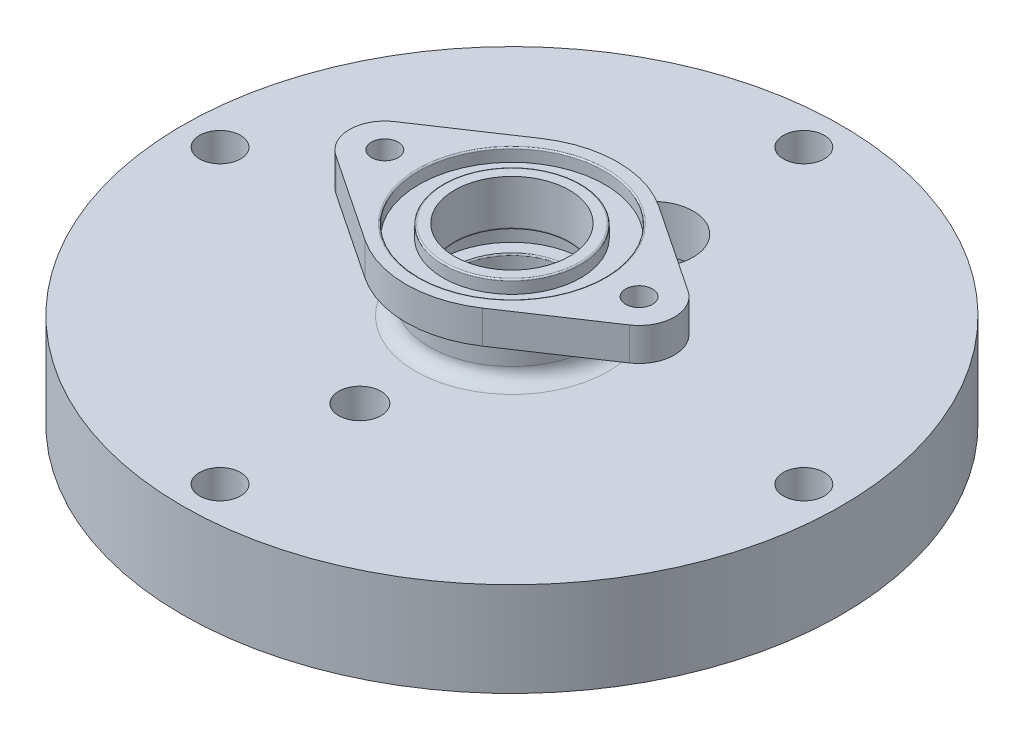
SolidWorks part; units mm, degrees
material "ABS"
ref_plane "Ön Düzlem" through (0, 0, 0) normal (0, 0, 1) x (1, 0, 0)
ref_plane "Üst Düzlem" through (0, 0, 0) normal (0, 1, 0) x (1, 0, 0)
ref_plane "Sağ Düzlem" through (0, 0, 0) normal (1, 0, 0) x (0, 0, -1)
sketch "Çizim1" plane through (0, 0, 0) normal (0, 1, 0) x (1, 0, 0)
  circle A0 centre (0, 0) radius 70
  dimension "D1" = 140
extrude "Yükseklik-Ekstrüzyon1" add sketch "Çizim1" along normal blind 20
sketch "Çizim2" plane through (0, 0, 0) normal (0, -1, 0) x (1, 0, 0)
  circle A0 centre (0, 0) radius 50.03
  circle A1 centre (0, 0) radius 45
  circle A2 centre (0, 0) radius 41
  circle A3 centre (0, 0) radius 17.35
  dimension "D1" = 100.06
  dimension "D2" = 90
  dimension "D3" = 82
  dimension "D4" = 34.7
extrude "Kes-Ekstrüzyon1" cut sketch "Çizim2" against normal blind 10 contours A0 A1 | A2 A3
sketch "Çizim4" plane through (0, 0, 0) normal (0, 0, 1) x (1, 0, 0)
  line L0 (-41, 0) -> (-13.6, 0)
  line L1 (-41, 0) -> (41, 0) construction
  line L2 (-45, 0) -> (45, 0) construction
  line L3 (-17.35, 0) -> (17.35, 0) construction
  line L4 (-17.35, 10) -> (-13.6, 0)
  line L8 (-17.35, 10) -> (17.35, 10) construction
  line L9 (-41, 10) -> (41, 10) construction
  line L10 (-17.35, 0) -> (-17.35, 10)
  line L11 (0, 0) -> (0, 30.5491)
  dimension "D1" = 27.4
revolve "Kes-Döndür1" cut sketch "Çizim4" angle 360 about L11
sketch "Çizim5" plane through (0, 20, 0) normal (0, 1, 0) x (1, 0, 0)
  circle A0 centre (0, 0) radius 17.5
  dimension "D1" = 35
extrude "Yükseklik-Ekstrüzyon2" add sketch "Çizim5" along normal blind 10
sketch "Çizim7" plane through (0, 30, 0) normal (0, 1, 0) x (1, 0, 0)
  line L2 (31.1667, -6.2361) -> (12.5, -18.7083)
  line L3 (31.1667, 6.2361) -> (12.5, 18.7083)
  line L4 (-12.5, -18.7083) -> (-31.1667, -6.2361)
  line L5 (-12.5, 18.7083) -> (-31.1667, 6.2361)
  arc A0 (12.5, 18.7083) -> (-12.5, 18.7083) centre (0, 0) ccw
  circle A1 centre (-27, 0) radius 2.85
  arc A2 (-31.1667, 6.2361) -> (-31.1667, -6.2361) centre (-27, 0) ccw
  circle A3 centre (27, 0) radius 2.85
  arc A4 (31.1667, -6.2361) -> (31.1667, 6.2361) centre (27, 0) ccw
  arc A5 (-12.5, -18.7083) -> (12.5, -18.7083) centre (0, 0) ccw
  dimension "D1" = 45
  dimension "D3" = 5.7
  dimension "D6" = 5.7
  dimension "D2" = 27
  dimension "D5" = 27
extrude "Yükseklik-Ekstrüzyon3" add sketch "Çizim7" along normal blind 7
sketch "Çizim8" plane through (0, 37, 0) normal (0, 1, 0) x (1, 0, 0)
  circle A0 centre (0, 0) radius 12.2
  dimension "D1" = 24.4
extrude "Kes-Ekstrüzyon3" cut sketch "Çizim8" against normal through all
sketch "Çizim9" plane through (0, 37, 0) normal (0, 1, 0) x (1, 0, 0)
  circle A1 centre (0, 0) radius 14.62
  circle A3 centre (0, 0) radius 19.75
  dimension "D1" = 39.5
  dimension "D2" = 29.24
extrude "Kes-Ekstrüzyon4" cut sketch "Çizim9" against normal blind 2.75
fillet "Radyus1" radius 0.3 2 edges at (0, 37, 14.62) (0, 37, 19.75)
fillet "Radyus2" radius 3 2 edges at (0, 30, 17.5) (0, 20, 17.5)
sketch "Çizim10" plane through (0, 0, 0) normal (0, 0, 1) x (1, 0, 0)
  line L2 (-11.8293, 27.2319) -> (-11.8293, 22.7319)
  line L4 (-11.8293, 22.7319) -> (-15.24, 22.7319)
  line L5 (-15.24, 22.7319) -> (-15.24, 27.2319)
  line L6 (-15.24, 27.2319) -> (-11.8293, 27.2319)
  line L7 (0, 0) -> (0, 39.8793)
  dimension "D1" = 15.24
  dimension "D2" = 4.5
revolve "Kes-Döndür2" cut sketch "Çizim10" angle 360 about L7
sketch "Çizim11" plane through (0, 0, 0) normal (0, 0, 1) x (1, 0, 0)
  line L0 (-50, 7.375) -> (-50, 2.625)
  line L1 (-50, 2.625) -> (-52.75, 2.625)
  line L2 (-52.75, 2.625) -> (-52.75, 7.375)
  line L6 (-52.75, 7.375) -> (-50, 7.375)
  line L7 (0, 37) -> (0, -25.9971)
  line L8 (12.2, 37) -> (-12.2, 37) construction
  dimension "D1" = 2.75
  dimension "D2" = 4.75
  dimension "D3" = 50
sketch "Çizim12" plane through (0, 20, 0) normal (0, 1, 0) x (1, 0, 0)
  circle A2 centre (0, 62) radius 4.35
  circle A3 centre (62, 0) radius 4.35
  circle A4 centre (0, -62) radius 4.35
  circle A5 centre (-62, 0) radius 4.35
  point P15 (0, 0)
  dimension "D2" = 8.7
  dimension "D3" = 4
extrude "Kes-Ekstrüzyon5" cut sketch "Çizim12" against normal through all
sketch "Çizim13" plane through (0, 20, 0) normal (0, 1, 0) x (1, 0, 0)
  circle A0 centre (0, 30) radius 8.5
  dimension "D1" = 17
  dimension "D2" = 30
extrude "Kes-Ekstrüzyon6" cut sketch "Çizim13" against normal blind 10
sketch "Çizim14" plane through (0, 10, 0) normal (0, -1, 0) x (1, 0, 0)
  circle A0 centre (0, 0) radius 45
  circle A1 centre (0, 0) radius 50.03
extrude "Kes-Ekstrüzyon7" cut sketch "Çizim14" against normal blind 3
sketch "Çizim15" plane through (0, 10, 0) normal (0, -1, 0) x (1, 0, 0)
  circle A2 centre (0, 32.2986) radius 4.5
  dimension "D1" = 9
extrude "Kes-Ekstrüzyon9" cut sketch "Çizim15" against normal blind 10
sketch "Çizim16" plane through (0, 0, 0) normal (0, -1, 0) x (1, 0, 0)
  circle A0 centre (0, 0) radius 44.25
  circle A1 centre (0, 0) radius 51
  dimension "D1" = 88.5
  dimension "D2" = 102
extrude "Kes-Ekstrüzyon10" cut sketch "Çizim16" against normal up to surface (13 mm away) up to face at (0, 13, -45)
fillet "Radyus3" radius 0.3 2 edges at (0, 22.7319, -12.2) (0, 27.2319, 12.2)
